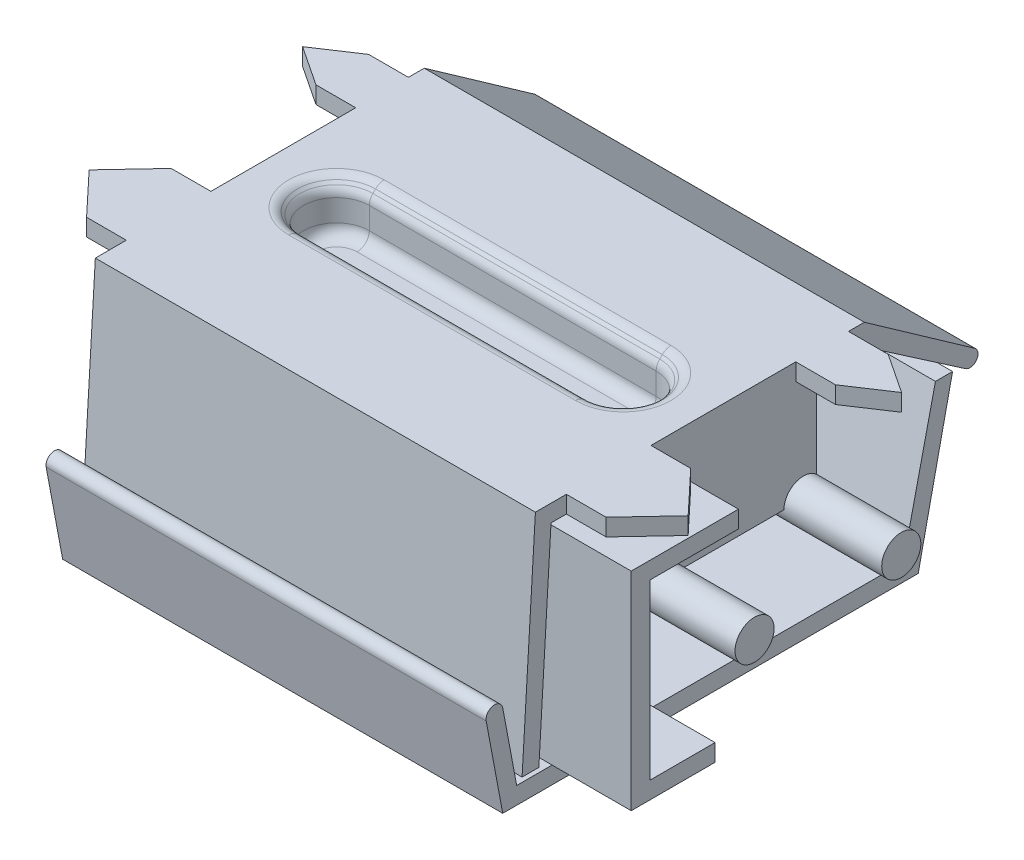
SolidWorks part; units mm, degrees
ref_plane "Plano frontal" through (0, 0, 0) normal (0, 0, 1) x (1, 0, 0)
ref_plane "Plano superior" through (0, 0, 0) normal (0, 1, 0) x (1, 0, 0)
ref_plane "Plano direito" through (0, 0, 0) normal (1, 0, 0) x (0, 0, -1)
sketch "Esboço1" plane through (0, 0, 0) normal (1, 0, 0) x (0, 0, -1)
  line L0 (1.7652, 0) -> (-1.7652, 0)
  line L1 (-4.65, -2.5) -> (3.8473, -2.5)
  line L2 (-4.2547, -2.0561) -> (-3.982, 2.5)
  line L3 (-3.982, 2.5) -> (2.7448, 2.5)
  line L4 (4.1995, 0.7255) -> (3.5415, -2.1495)
  line L5 (3.9223, -2.1495) -> (3.8473, -2.5)
  line L6 (-1.7652, 0) -> (-1.7652, 2.15)
  line L7 (2.7448, 2.5) -> (5, 0.9124)
  line L8 (-4.9881, -0.6974) -> (-4.65, -2.5)
  line L9 (-4.3647, -2.1495) -> (3.5415, -2.1495)
  line L11 (-4.65, -0.6339) -> (-4.3647, -2.1495)
  line L12 (-3.6627, 2.15) -> (-3.9115, -2.0561)
  line L13 (-4.2547, -2.0561) -> (-3.9115, -2.0561)
  line L14 (1.7652, 2.15) -> (2.6187, 2.15)
  line L15 (-1.7652, 2.15) -> (-3.6627, 2.15)
  line L16 (1.7652, 0) -> (1.7652, 2.15)
  line L18 (4.8116, 0.6448) -> (2.6187, 2.15)
  line L19 (4.5495, 0.7255) -> (4.1995, 0.7255)
  line L20 (-1.7652, -2.15) -> (-1.7652, -2.1495)
  line L22 (3.9223, -2.1495) -> (4.5495, 0.7255)
  line L25 (-1.7652, -2.15) -> (-1.7648, -2.1495) construction
  arc A0 (-4.9881, -0.6974) -> (-4.65, -0.6339) centre (-4.8191, -0.6657) cw
  arc A1 (5, 0.9124) -> (4.8116, 0.6448) centre (4.9058, 0.7786) cw
  point P0 (0, 0)
  point P3 (0, 0)
  dimension "D4" = 0.35
extrude "Ressalto-extrusão1" add sketch "Esboço1" along normal blind 9 contours A1 L7 L3 L2 L13 L12 L15 L6 L0 L16 L14 L18 | L1 L5 L22 L19 L4 L9 L11 A0 L8
sketch "Esboço2" plane through (0, 2.5, 0) normal (0, 1, 0) x (1, 0, 0)
  line L4 (1.5671, 0.0543) -> (7.4329, 0.0543)
  line L5 (1.5671, -1.2914) -> (7.4329, -1.2914)
  arc A0 (1.5671, 0.0543) -> (1.5671, -1.2914) centre (1.5671, -0.6186) ccw
  arc A1 (7.4329, -1.2914) -> (7.4329, 0.0543) centre (7.4329, -0.6186) ccw
  point P8 (4.5, -0.6186)
extrude "Corte-extrusão1" cut sketch "Esboço2" against normal blind 1
chamfer "Chanfro1" distance 0.2 angle 45 4 edges at (4.5, 2.5, -0.0543) (0.8943, 2.5, 0.6186) (8.1057, 2.5, 0.6186) (4.5, 2.5, 1.2914)
fillet "Filete1" radius 0.25 4 edges at (0.6943, 2.5, 0.6186) (4.5, 2.5, 1.4914) (8.3057, 2.5, 0.6186) (4.5, 2.5, -0.2543)
fillet "Filete2" radius 0.25 4 edges at (8.1057, 2.3, 0.6186) (4.5, 2.3, 1.2914) (0.8943, 2.3, 0.6186) (4.5, 2.3, -0.0543)
fillet "Filete3" radius 0.25 4 edges at (8.1057, 1.5, 0.6186) (4.5, 1.5, 1.2914) (0.8943, 1.5, 0.6186) (4.5, 1.5, -0.0543)
sketch "Esboço3" plane through (9, 0, 0) normal (1, 0, 0) x (0, 0, -1)
  line L0 (1.7652, 0) -> (-1.7652, 0) construction
  circle A0 centre (1.5, 0) radius 0.4
  circle A1 centre (-1.5, 0) radius 0.4
  dimension "D1" = 0.8
  dimension "D2" = 0.8
  dimension "D3" = 3
extrude "Ressalto-extrusão2" add sketch "Esboço3" against normal blind 12 and the other way blind 3
sketch "Esboço4" plane through (0, 2.9636, -2.0864) normal (0, 0.8177, -0.5757) x (1, 0, 0)
  line L4 (11, 6.2502) -> (12.4628, 6.2502)
  line L6 (-2, -11.3109) -> (-2, 6.2502)
  line L8 (11, -11.3109) -> (11, 6.2502)
  line L12 (-3.4628, -11.3109) -> (-3.4628, 6.2502)
  line L14 (12.4628, -11.3109) -> (12.4628, 6.2502)
  line L17 (11, -11.3109) -> (12.4628, -11.3109)
  line L18 (-2, -11.3109) -> (-3.4628, -11.3109)
  line L19 (-2, 6.2502) -> (-3.4628, 6.2502)
  dimension "D1" = 13
extrude "Corte-extrusão3" cut sketch "Esboço4" against normal blind 12
sketch "Esboço5" plane through (9, 0, 0) normal (1, 0, 0) x (0, 0, -1)
  line L0 (-3.6627, 2.1169) -> (-3.6627, -2.1278)
  line L1 (-3.6627, -2.1278) -> (-1.9475, -2.1278)
  line L2 (-1.9475, -2.1278) -> (-1.9475, -1.7778)
  line L6 (-1.9475, -1.7778) -> (-3.2758, -1.7778)
  line L8 (-3.2758, -1.7778) -> (-3.2758, 1.7669)
  line L9 (-3.982, 2.5) -> (2.7448, 2.5) construction
  line L10 (-3.3485, 2.15) -> (-1.6184, 2.15)
  line L11 (-3.3485, 2.15) -> (-3.3485, 2.5)
  line L12 (-3.3485, 2.5) -> (-1.6184, 2.5)
  line L13 (-3.2758, 1.7669) -> (-1.4697, 1.7669)
  line L14 (-1.6184, 2.15) -> (-1.6184, 2.5)
  line L15 (-3.6627, 2.1169) -> (-1.4697, 2.1169)
  line L16 (1.3427, 2.15) -> (2.4205, 2.15)
  line L17 (1.3427, 2.15) -> (1.3427, 2.5)
  line L18 (-1.4697, 2.1169) -> (-1.4697, 1.7669)
  line L19 (1.3427, 2.5) -> (2.4205, 2.5)
  line L20 (2.4205, 2.15) -> (2.4205, 2.5)
  point P6 (1.8816, 2.325)
  dimension "D1" = 0.35
  dimension "D2" = 0.35
extrude "Ressalto-extrusão3" add sketch "Esboço5" against normal blind 12 and the other way blind 4
sketch "Esboço7" plane through (0, 2.5, 0) normal (0, 1, 0) x (1, 0, 0)
  line L0 (9, 2.7448) -> (0, 2.7448) construction
  line L1 (10.625, -8.4233) -> (15.0733, -8.4233)
  line L2 (-1.625, -5.8205) -> (-1.625, 11.3102)
  line L4 (10.625, -5.8205) -> (10.625, 11.3102)
  line L5 (10.9136, 13.913) -> (15.0733, 13.913)
  line L7 (10.625, 11.3102) -> (10.9136, 13.913)
  line L8 (-6.0733, -8.4233) -> (-1.625, -8.4233)
  line L9 (-6.0733, -8.4233) -> (-6.0733, 13.913)
  line L10 (-6.0733, 13.913) -> (-1.3007, 13.913)
  line L11 (15.0733, -8.4233) -> (15.0733, 13.913)
  line L14 (-1.625, 11.3102) -> (-1.3007, 13.913)
  line L15 (-1.625, -5.8205) -> (-1.625, -8.4233)
  line L16 (10.625, -5.8205) -> (10.625, -8.4233)
  point P0 (4.5, 2.7448)
  point P7 (4.5, 2.7448)
  dimension "D1" = 12.25
extrude "Corte-extrusão6" cut sketch "Esboço7" against normal blind 0.36
sketch "Esboço11" plane through (13, 0, 0) normal (1, 0, 0) x (0, 0, -1)
  line L0 (-3.6627, 2.1169) -> (-1.4697, 2.1169)
  line L1 (-1.4697, 2.1169) -> (-1.4697, 1.7669)
  line L2 (-1.4697, 1.7669) -> (-3.2758, 1.7669)
  line L3 (-3.2758, 1.7669) -> (-3.2758, -1.7778)
  line L4 (-3.2758, -1.7778) -> (-1.9475, -1.7778)
  line L5 (-1.9475, -1.7778) -> (-1.9475, -2.1278)
  line L6 (-1.9475, -2.1278) -> (-3.6627, -2.1278)
  line L7 (-3.6627, -2.1278) -> (-3.6627, 2.1169)
extrude "Corte-extrusão8" cut sketch "Esboço11" against normal blind 2.36
sketch "Esboço12" plane through (-3, 0, 0) normal (-1, 0, 0) x (0, 0, 1)
  line L0 (1.4697, 2.1169) -> (1.4697, 1.7669)
  line L1 (1.4697, 1.7669) -> (3.2758, 1.7669)
  line L2 (3.2758, 1.7669) -> (3.2758, -1.7778)
  line L3 (3.2758, -1.7778) -> (1.9475, -1.7778)
  line L4 (1.9475, -1.7778) -> (1.9475, -2.1278)
  line L5 (1.9475, -2.1278) -> (1.9475, -1.7778) construction
  line L6 (1.9475, -2.1278) -> (3.6627, -2.1278)
  line L7 (3.6627, -2.1278) -> (3.6627, 2.1169)
  line L8 (3.6627, 2.1169) -> (1.4697, 2.1169)
extrude "Corte-extrusão9" cut sketch "Esboço12" against normal blind 3
sketch "Esboço13" plane through (0, 2.5, 0) normal (0, 1, 0) x (1, 0, 0)
  line L0 (-1.625, 1.8816) -> (-0.8125, 2.4205)
  line L1 (-1.625, 1.3427) -> (-1.625, 2.4205) construction
  line L2 (0, 2.4205) -> (-1.625, 2.4205) construction
  line L3 (-1.625, 1.8816) -> (-0.8125, 1.3427)
  line L4 (0, 1.3427) -> (-1.625, 1.3427) construction
  line L5 (-1.625, -2.4835) -> (-0.8125, -1.6184)
  line L6 (-1.625, -3.3485) -> (-1.625, -1.6184) construction
  line L7 (0, -1.6184) -> (-1.625, -1.6184) construction
  line L8 (-1.625, -2.4835) -> (-0.8125, -3.3485)
  line L9 (0, -3.3485) -> (-1.625, -3.3485) construction
  line L10 (-0.8125, 2.4205) -> (-0.6194, 3.4169)
  line L11 (-0.6194, 3.4169) -> (-2.7003, 2.9187)
  line L12 (-2.7003, 2.9187) -> (-3.1886, 0.3993)
  line L13 (-3.1886, 0.3993) -> (-0.8125, 0.2201)
  line L14 (-0.8125, 0.2201) -> (-0.8125, 1.3427)
  line L15 (-0.8125, -1.6184) -> (-1.509, -0.4283)
  line L16 (-1.509, -0.4283) -> (-2.9717, -0.8354)
  line L17 (-2.9717, -0.8354) -> (-2.8058, -2.916)
  line L18 (-2.8058, -2.916) -> (-2.5665, -4.1819)
  line L19 (-2.5665, -4.1819) -> (-1.625, -4.379)
  line L20 (-1.625, -4.379) -> (-0.8125, -3.3485)
extrude "Corte-extrusão10" cut sketch "Esboço13" against normal blind 0.36
sketch "Esboço14" plane through (0, 2.5, 0) normal (0, 1, 0) x (1, 0, 0)
  line L0 (10.625, 1.8816) -> (9.8125, 2.4205)
  line L1 (10.625, 2.4205) -> (10.625, 1.3427) construction
  line L2 (10.625, 2.4205) -> (9, 2.4205) construction
  line L3 (9.8125, 2.4205) -> (9.8125, 3.3838)
  line L4 (10.625, 1.8816) -> (9.8125, 1.3427)
  line L5 (9.8125, 3.3838) -> (12.1787, 2.5768)
  line L6 (12.1787, 2.5768) -> (12.2905, 0.9131)
  line L7 (12.2905, 0.9131) -> (10.1426, 0.1805)
  line L8 (10.1426, 0.1805) -> (9.8125, 1.3427)
  line L9 (10.625, -2.4835) -> (9.8125, -1.6184)
  line L10 (10.625, -1.6184) -> (10.625, -3.3485) construction
  line L11 (10.625, -1.6184) -> (9, -1.6184) construction
  line L12 (10.625, -2.4835) -> (9.8125, -3.3485)
  line L13 (10.625, -3.3485) -> (9, -3.3485) construction
  line L14 (9.8125, -1.6184) -> (9.8125, -0.8376)
  line L15 (9.8125, -0.8376) -> (12.8864, -1.3963)
  line L16 (12.8864, -1.3963) -> (11.8187, -3.3485)
  line L17 (11.8187, -3.3485) -> (10.5274, -4.0284)
  line L18 (10.5274, -4.0284) -> (9.8125, -3.3485)
extrude "Corte-extrusão11" cut sketch "Esboço14" against normal blind 0.36
